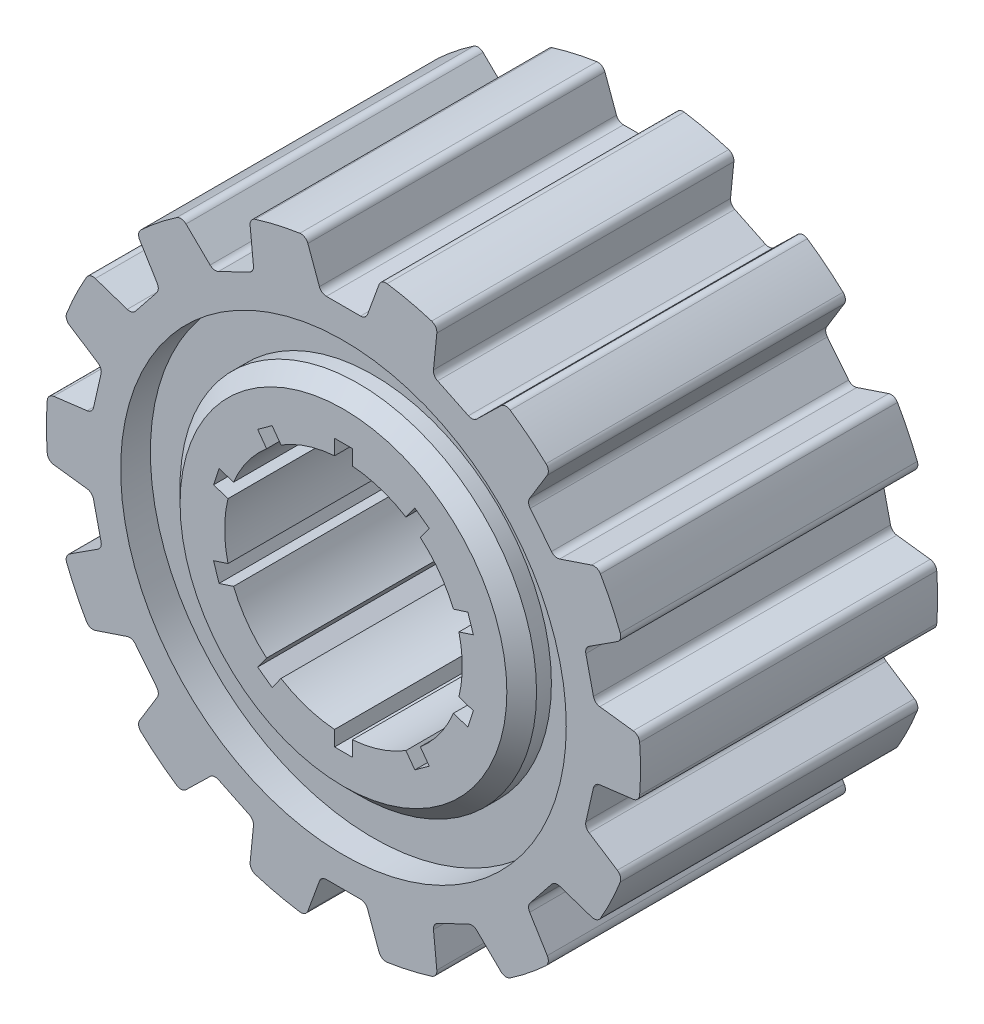
SolidWorks part; units mm, degrees
ref_plane "Front Plane" through (0, 0, 0) normal (0, 0, 1) x (1, 0, 0)
ref_plane "Top Plane" through (0, 0, 0) normal (0, 1, 0) x (1, 0, 0)
ref_plane "Right Plane" through (0, 0, 0) normal (1, 0, 0) x (0, 0, -1)
sketch "Sketch2" plane through (0, 0, 0) normal (0, 0, 1) x (1, 0, 0)
  line L0 (2.1018, 3.4033) -> (2.4023, 3.8169)
  line L2 (0.3, 3.9887) -> (0.3, 4.5)
  line L3 (0.3, 4.5) -> (-0.3, 4.5)
  line L4 (-0.3, 3.9887) -> (-0.3, 4.5)
  line L5 (2.8877, 3.4642) -> (2.4023, 3.8169)
  line L6 (2.5872, 3.0506) -> (2.8877, 3.4642)
  line L7 (3.7008, 1.5179) -> (4.187, 1.6759)
  line L8 (4.3725, 1.1053) -> (4.187, 1.6759)
  line L9 (3.8862, 0.9473) -> (4.3725, 1.1053)
  line L10 (3.8862, -0.9473) -> (4.3725, -1.1053)
  line L11 (4.187, -1.6759) -> (4.3725, -1.1053)
  line L12 (3.7008, -1.5179) -> (4.187, -1.6759)
  line L13 (2.5872, -3.0506) -> (2.8877, -3.4642)
  line L14 (2.4023, -3.8169) -> (2.8877, -3.4642)
  line L15 (2.1018, -3.4033) -> (2.4023, -3.8169)
  line L16 (0.3, -3.9887) -> (0.3, -4.5)
  line L17 (-0.3, -4.5) -> (0.3, -4.5)
  line L18 (-0.3, -3.9887) -> (-0.3, -4.5)
  line L19 (-2.1018, -3.4033) -> (-2.4023, -3.8169)
  line L20 (-2.8877, -3.4642) -> (-2.4023, -3.8169)
  line L21 (-2.5872, -3.0506) -> (-2.8877, -3.4642)
  line L22 (-3.7008, -1.5179) -> (-4.187, -1.6759)
  line L23 (-4.3725, -1.1053) -> (-4.187, -1.6759)
  line L24 (-3.8862, -0.9473) -> (-4.3725, -1.1053)
  line L25 (-3.8862, 0.9473) -> (-4.3725, 1.1053)
  line L26 (-4.187, 1.6759) -> (-4.3725, 1.1053)
  line L27 (-3.7008, 1.5179) -> (-4.187, 1.6759)
  line L28 (-2.5872, 3.0506) -> (-2.8877, 3.4642)
  line L29 (-2.4023, 3.8169) -> (-2.8877, 3.4642)
  line L30 (-2.1018, 3.4033) -> (-2.4023, 3.8169)
  arc A0 (-0.3, 3.9887) -> (-2.1018, 3.4033) centre (0, 0) ccw
  circle A1 centre (0, 0) radius 10
  arc A2 (-2.5872, 3.0506) -> (-3.7008, 1.5179) centre (0, 0) ccw
  arc A3 (-3.8862, 0.9473) -> (-3.8862, -0.9473) centre (0, 0) ccw
  arc A4 (-3.7008, -1.5179) -> (-2.5872, -3.0506) centre (0, 0) ccw
  arc A5 (-2.1018, -3.4033) -> (-0.3, -3.9887) centre (0, 0) ccw
  arc A6 (0.3, -3.9887) -> (2.1018, -3.4033) centre (0, 0) ccw
  arc A7 (2.5872, -3.0506) -> (3.7008, -1.5179) centre (0, 0) ccw
  arc A8 (3.8862, -0.9473) -> (3.8862, 0.9473) centre (0, 0) ccw
  arc A9 (3.7008, 1.5179) -> (2.5872, 3.0506) centre (0, 0) ccw
  arc A10 (2.1018, 3.4033) -> (0.3, 3.9887) centre (0, 0) ccw
  point P4 (0, 4)
  dimension "D1" = 8
  dimension "D2" = 20
  dimension "D3" = 0.6
  dimension "D4" = 4.5
  dimension "D5" = 0.5113
  dimension "D6" = 10
extrude "Boss-Extrude1" add sketch "Sketch2" along normal mid plane 10
sketch "Sketch3" plane through (0, 0, 5) normal (0, 0, 1) x (1, 0, 0)
  line L0 (0, 0) -> (0, 10) construction
  line L1 (-0.75, 8.5) -> (0.75, 8.5)
  line L2 (0.75, 8.5) -> (1.2666, 9.9195)
  line L3 (-0.75, 8.5) -> (-1.2666, 9.9195)
  circle A0 centre (0, 0) radius 10 construction
  arc A1 (-1.2666, 9.9195) -> (1.2666, 9.9195) centre (0, 9.116) cw
  point P11 (0, 8.5)
  dimension "D4" = 1.5
  dimension "D1" = 0.75
  dimension "D2" = 20
  dimension "D3" = 8.5
extrude "Cut-Extrude1" cut sketch "Sketch3" against normal through all
pattern_circular "CirPattern1" count 14 over 360 about axis through (0, 0, 0) along (0, 0, 1) of "Cut-Extrude1"
sketch "Sketch4" plane through (0, 0, 5) normal (0, 0, 1) x (1, 0, 0)
  circle A0 centre (0, 0) radius 7.5
  circle A1 centre (0, 0) radius 6
  dimension "D1" = 15
  dimension "D2" = 12
extrude "Cut-Extrude2" cut sketch "Sketch4" against normal blind 1
chamfer "Chamfer1" distance 0.5 angle 45 1 edges at (6, 0, 5)
mirror "Mirror1" about plane through (0, 0, 0) normal (0, 0, 1) of "Cut-Extrude2"
chamfer "Chamfer2" distance 0.5 angle 45 1 edges at (6, 0, -5)
fillet "Fillet1" radius 0.25 56 edges at (-7.1132, 4.7133, 0) (-8.5451, 5.1944, 0) (-9.3889, 3.4422, 0) (-8.12, 2.6226, 0) (-8.4538, 1.1602, 0) (-9.9526, 0.9724, 0) (-9.9526, -0.9724, 0) (-8.4538, -1.1602, 0) (-8.12, -2.6226, 0) (-9.3889, -3.4422, 0) (-8.5451, -5.1944, 0) (-7.1132, -4.7133, 0) (-6.178, -5.886, 0) (-6.9656, -7.175, 0) (-5.4451, -8.3875, 0) (-4.3637, -7.3328, 0) (-3.0123, -7.9836, 0) (-3.1627, -9.4867, 0) (-1.2666, -9.9195, 0) (-0.75, -8.5, 0) (0.75, -8.5, 0) (1.2666, -9.9195, 0) (3.1627, -9.4867, 0) (3.0123, -7.9836, 0) (4.3637, -7.3328, 0) (5.4451, -8.3875, 0) (6.9656, -7.175, 0) (6.178, -5.886, 0) (7.1132, -4.7133, 0) (8.5451, -5.1944, 0) (9.3889, -3.4422, 0) (8.12, -2.6226, 0) (8.4538, -1.1602, 0) (9.9526, -0.9724, 0) (9.9526, 0.9724, 0) (8.4538, 1.1602, 0) (8.12, 2.6226, 0) (9.3889, 3.4422, 0) (8.5451, 5.1944, 0) (7.1132, 4.7133, 0) (6.178, 5.886, 0) (6.9656, 7.175, 0) (5.4451, 8.3875, 0) (4.3637, 7.3328, 0) (3.0123, 7.9836, 0) (1.2666, 9.9195, 0) (0.75, 8.5, 0) (-0.75, 8.5, 0) (-1.2666, 9.9195, 0) (-3.1627, 9.4867, 0) (-3.0123, 7.9836, 0) (-4.3637, 7.3328, 0) (-5.4451, 8.3875, 0) (-6.9656, 7.175, 0) (-6.178, 5.886, 0) (3.1627, 9.4867, 0)
